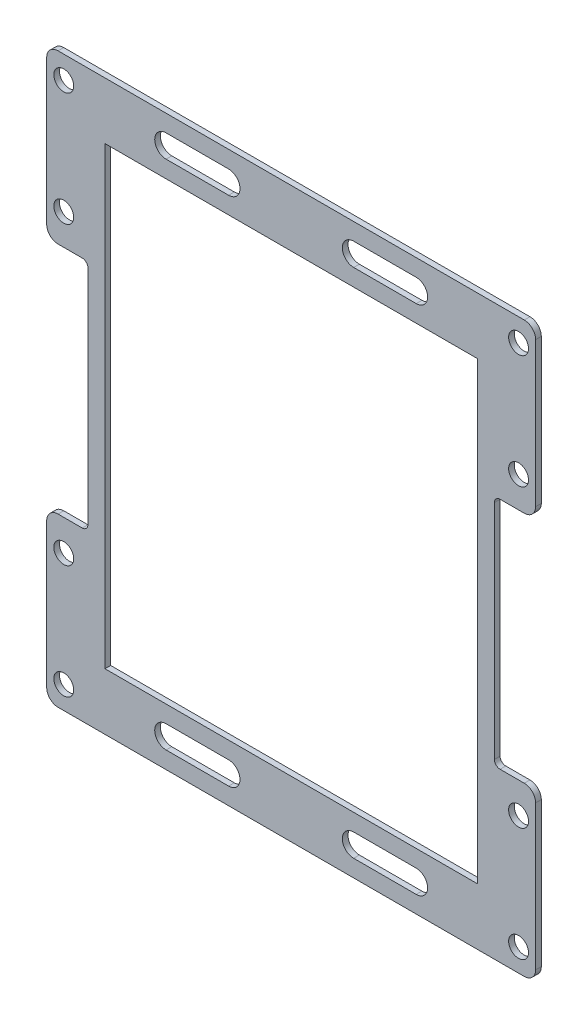
SolidWorks part; units mm, degrees
ref_plane "前基準面" through (0, 0, 0) normal (0, 0, 1) x (1, 0, 0)
ref_plane "上基準面" through (0, 0, 0) normal (0, 1, 0) x (1, 0, 0)
ref_plane "右基準面" through (0, 0, 0) normal (1, 0, 0) x (0, 0, -1)
sketch "草圖1" plane through (0, 0, 0) normal (0, 0, 1) x (1, 0, 0)
  line L3 (-32.75, 40) -> (32.75, 40)
  line L6 (-32.75, 40) -> (-32.75, -40)
  line L9 (-32.75, -40) -> (32.75, -40)
  line L12 (-167.459, 0) -> (250.2577, 0) construction
  line L13 (0, 741.9689) -> (0, -704.7384) construction
  line L16 (32.75, 40) -> (32.75, -40)
  line L19 (-32.75, 40) -> (32.75, -40) construction
  line L22 (-32.75, -40) -> (32.75, 40) construction
  line L34 (-22, -45) -> (-11, -45) construction
  line L35 (-22, -43) -> (-11, -43)
  line L36 (-22, -47) -> (-11, -47)
  line L37 (22, -45) -> (11, -45) construction
  line L38 (22, -43) -> (11, -43)
  line L39 (22, -47) -> (11, -47)
  line L40 (22, 45) -> (11, 45) construction
  line L41 (22, 43) -> (11, 43)
  line L42 (22, 47) -> (11, 47)
  line L43 (-22, 45) -> (-11, 45) construction
  line L44 (-22, 43) -> (-11, 43)
  line L45 (-22, 47) -> (-11, 47)
  line L46 (-35.75, -20.5625) -> (-43, -20.5625)
  line L47 (-25.75, -50) -> (25.75, -50)
  line L48 (-35.75, -20.5625) -> (-35.75, 20.5625)
  line L49 (-25.75, 50) -> (25.75, 50)
  line L50 (35.75, -20.5625) -> (35.75, 20.5625)
  line L51 (-35.75, -50) -> (35.75, 50) construction
  line L52 (-35.75, 50) -> (35.75, -50) construction
  line L61 (-43, -20.5625) -> (-43, -50)
  line L62 (-43, -50) -> (-25.75, -50)
  line L63 (43, -50) -> (25.75, -50)
  line L64 (43, -20.5625) -> (43, -50)
  line L65 (35.75, -20.5625) -> (43, -20.5625)
  line L66 (35.75, 20.5625) -> (43, 20.5625)
  line L67 (43, 20.5625) -> (43, 50)
  line L68 (43, 50) -> (25.75, 50)
  line L69 (-43, 50) -> (-25.75, 50)
  line L70 (-43, 20.5625) -> (-43, 50)
  line L71 (-35.75, 20.5625) -> (-43, 20.5625)
  arc A27 (-22, -43) -> (-22, -47) centre (-22, -45) ccw
  arc A28 (-11, -47) -> (-11, -43) centre (-11, -45) ccw
  arc A29 (22, -43) -> (22, -47) centre (22, -45) cw
  arc A30 (11, -47) -> (11, -43) centre (11, -45) cw
  arc A31 (22, 43) -> (22, 47) centre (22, 45) ccw
  arc A32 (11, 47) -> (11, 43) centre (11, 45) ccw
  arc A33 (-22, 43) -> (-22, 47) centre (-22, 45) cw
  arc A34 (-11, 47) -> (-11, 43) centre (-11, 45) cw
  circle A48 centre (-40, -26) radius 1.75
  circle A49 centre (40, -26) radius 1.75
  circle A50 centre (40, 26) radius 1.75
  circle A51 centre (-40, 26) radius 1.75
  circle A52 centre (-40, -46) radius 1.75
  circle A53 centre (-40, 46) radius 1.75
  circle A54 centre (40, 46) radius 1.75
  circle A55 centre (40, -46) radius 1.75
  point P0 (0, 0)
  point P87 (-16.5, -45)
  point P94 (16.5, -45)
  point P101 (16.5, 45)
  point P108 (-16.5, 45)
  dimension "D4" = 3
  dimension "D6" = 45
  dimension "D10" = 2
  dimension "D5" = 80
  dimension "D25" = 52
  dimension "D27" = 3.5
  dimension "D28" = 46
  dimension "D29" = 3.5
  dimension "D16" = 71.5
  dimension "D17" = 100
  dimension "D22" = 22
  dimension "D23" = 11
  dimension "D26" = 40
  dimension "D30" = 43
extrude "填料-伸長1" add sketch "草圖1" along normal blind 1
fillet "圓角1" radius 1 4 edges at (35.75, -20.5625, 0.5) (35.75, 20.5625, 0.5) (-35.75, 20.5625, 0.5) (-35.75, -20.5625, 0.5)
fillet "圓角2" radius 2 8 edges at (43, 20.5625, 0.5) (43, 50, 0.5) (-43, 50, 0.5) (-43, 20.5625, 0.5) (-43, -20.5625, 0.5) (-43, -50, 0.5) (43, -50, 0.5) (43, -20.5625, 0.5)
